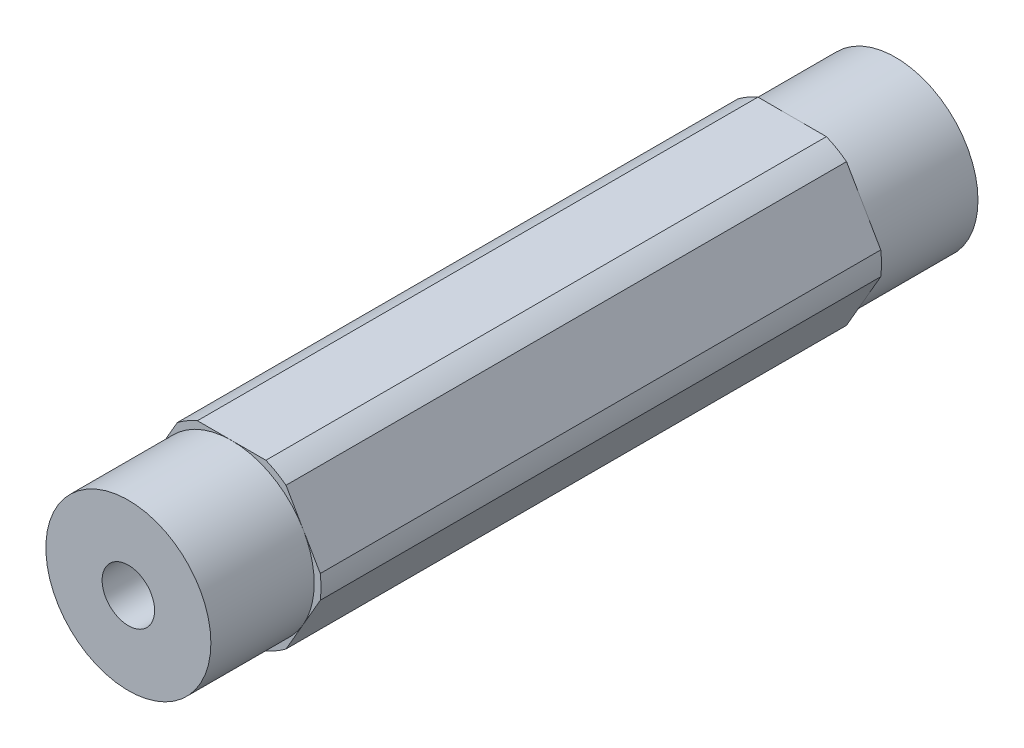
SolidWorks part; units mm, degrees
ref_plane "Front Plane" through (0, 0, 0) normal (0, 0, 1) x (1, 0, 0)
ref_plane "Top Plane" through (0, 0, 0) normal (0, 1, 0) x (1, 0, 0)
ref_plane "Right Plane" through (0, 0, 0) normal (1, 0, 0) x (0, 0, -1)
sketch "Sketch1" plane through (0, 0, 0) normal (0, 0, 1) x (1, 0, 0)
  line L1 (7.3323, 0) -> (3.6662, 6.35)
  line L2 (3.6662, 6.35) -> (-3.6662, 6.35)
  line L3 (-3.6662, 6.35) -> (-7.3323, 0)
  line L4 (-7.3323, 0) -> (-3.6662, -6.35)
  line L5 (-3.6662, -6.35) -> (3.6662, -6.35)
  line L6 (3.6662, -6.35) -> (7.3323, 0)
  circle A1 centre (0, 0) radius 6.35 construction
  dimension "D1" = 12.7
extrude "Boss-Extrude1" add sketch "Sketch1" along normal mid plane 59.0347 contours L3 L4 L5 L6 L1 L2
sketch "Sketch2" plane through (0, 0, 29.5173) normal (0, 0, 1) x (1, 0, 0)
  circle A0 centre (0, 0) radius 6.35
extrude "Cut-Extrude2" cut sketch "Sketch2" against normal blind 7.9502 flip side to cut
sketch "Sketch3" plane through (0, 0, 29.5173) normal (0, 0, 1) x (1, 0, 0)
  circle A0 centre (0, 0) radius 6.875
  dimension "D1" = 13.75
extrude "Cut-Extrude4" cut sketch "Sketch3" against normal through all flip side to cut
mirror "Mirror1" about plane through (0, 0, 0) normal (0, 0, 1) of "Cut-Extrude2"
sketch "Sketch4" plane through (0, 0, 29.5173) normal (0, 0, 1) x (1, 0, 0)
  circle A0 centre (0, 0) radius 2.0193
  dimension "D1" = 4.0386
extrude "Cut-Extrude5" cut sketch "Sketch4" against normal through all
equation "\"D1@Boss-Extrude1\"=1.75670+(2*(1/4))+(2*1/16)+0.005-1/16"
